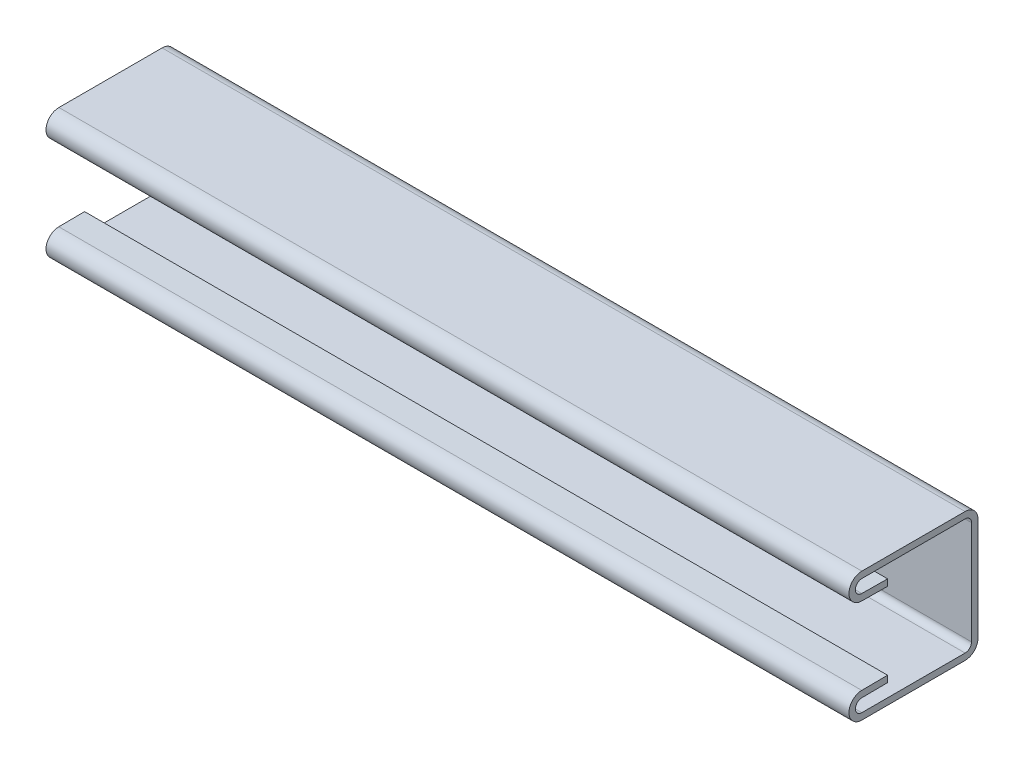
SolidWorks part; units mm, degrees
ref_plane "Plane1" through (0, 0, 0) normal (0, 0, 1) x (1, 0, 0)
ref_plane "Plane2" through (0, 0, 0) normal (0, 1, 0) x (1, 0, 0)
ref_plane "Plane3" through (0, 0, 0) normal (1, 0, 0) x (0, 0, -1)
sketch "Sketch1" plane through (0, 0, 0) normal (0, 0, 1) x (1, 0, 0)
  line L0 (0, 0) -> (-124.4577, 0)
other "ABC"
ref_plane "Plane4" through (0, 0, 0) normal (-1, 0, 0) x (0, -1, 0)
sketch "Sketch15" plane through (0, 0, 0) normal (-1, 0, 0) x (0, -1, 0)
  line L0 (-8, -9) -> (8, -9)
  line L1 (9, -8) -> (9, 8)
  line L2 (7, 8.0087) -> (6.9651, 4.0089)
  line L3 (-7, 8.0087) -> (-6.9651, 4.0089)
  line L4 (-9, -8) -> (-9, 8)
  line L5 (-6.0001, 8.0175) -> (-5.9652, 4.0176)
  line L6 (-10, -8) -> (-10, 8)
  line L7 (-8, -10) -> (8, -10)
  line L8 (10, -8) -> (10, 8)
  line L9 (6.0001, 8.0175) -> (5.9652, 4.0176)
  line L10 (-6.0001, 8.0175) -> (-5.9125, -2.0191) construction
  line L11 (-7, 8.0087) -> (-6.9125, -2.0279) construction
  line L12 (0, -10.6817) -> (0, 11.3464) construction
  line L13 (5.9652, 4.0176) -> (6.9651, 4.0089)
  line L14 (-5.9652, 4.0176) -> (-6.9651, 4.0089)
  arc A0 (9, 8) -> (7, 8.0087) centre (8, 8) ccw
  arc A1 (9, -8) -> (8, -9) centre (8, -8) cw
  arc A2 (-9, -8) -> (-8, -9) centre (-8, -8) ccw
  arc A3 (-9, 8) -> (-7, 8.0087) centre (-8, 8) cw
  arc A4 (-10, 8) -> (-6.0001, 8.0175) centre (-8, 8) cw
  arc A5 (-10, -8) -> (-8, -10) centre (-8, -8) ccw
  arc A6 (10, -8) -> (8, -10) centre (8, -8) cw
  arc A7 (10, 8) -> (6.0001, 8.0175) centre (8, 8) ccw
  point P15 (0, 0)
  dimension "D3" = 0.5
  dimension "D2" = 1
  dimension "D1" = 1
  dimension "D6" = 20
  dimension "D9" = 6
  dimension "D4" = 1
  dimension "D5" = 20
  dimension "D7" = 10
  dimension "D8" = 4
  dimension "D10" = 4.0348
equation "\"D7@Sketch15\" = \"D6@Sketch15\" / 2"
